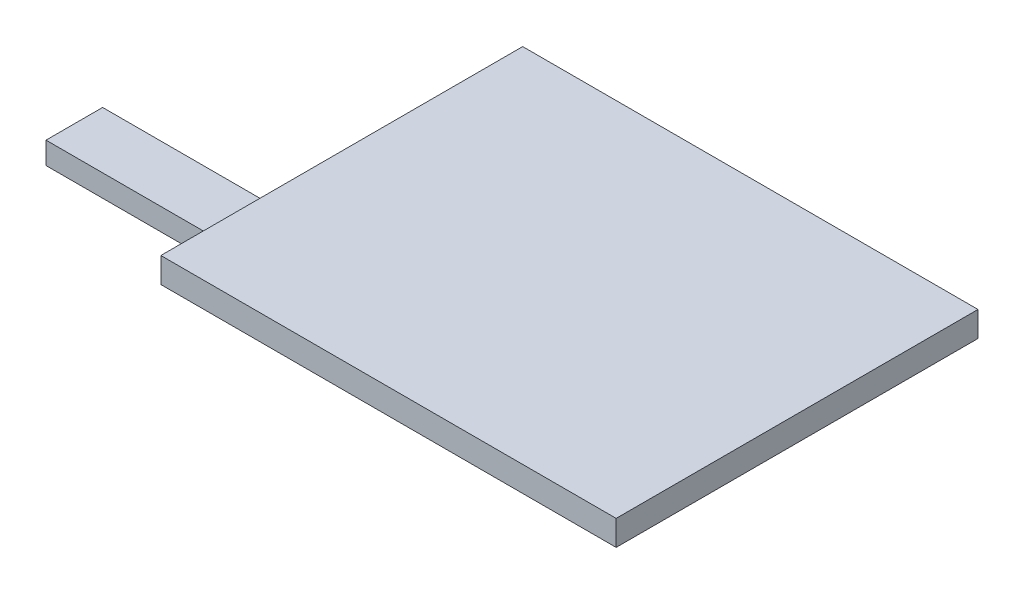
SolidWorks part; units mm, degrees
ref_plane "Front Plane" through (0, 0, 0) normal (0, 0, 1) x (1, 0, 0)
ref_plane "Top Plane" through (0, 0, 0) normal (0, 1, 0) x (1, 0, 0)
ref_plane "Right Plane" through (0, 0, 0) normal (1, 0, 0) x (0, 0, -1)
sketch "Sketch1" plane through (0, 0, 0) normal (0, 0, 1) x (1, 0, 0)
  line L0 (-37.4502, 11.0728) -> (107.2498, 11.0728)
  line L1 (107.2498, 11.0728) -> (107.2498, 3.0728)
  line L2 (107.2498, 3.0728) -> (-37.4502, 3.0728)
  line L3 (-37.4502, 3.0728) -> (-37.4502, 11.0728)
  dimension "D1" = 8
  dimension "D2" = 144.7
extrude "Boss-Extrude1" add sketch "Sketch1" along normal blind 115
sketch "Sketch2" plane through (0, 11.0728, 0) normal (0, 1, 0) x (1, 0, 0)
  line L0 (-37.4502, -57.5) -> (107.2498, -57.5) construction
  line L1 (-37.4502, -115) -> (-37.4502, 0) construction
  line L2 (107.2498, -115) -> (107.2498, 0) construction
sketch "Sketch3" plane through (0, 3.0728, 0) normal (0, -1, 0) x (1, 0, 0)
  line L0 (-37.4502, 77.5) -> (-10.4789, 77.5) construction
  line L1 (-37.4502, 115) -> (-37.4502, 0) construction
  line L2 (-37.4502, 57.5) -> (107.2498, 57.5) construction
  line L3 (-37.4502, 86.5) -> (-27.4502, 86.5)
  line L4 (-27.4502, 86.5) -> (-27.4502, 68.5)
  line L5 (-27.4502, 68.5) -> (-37.4502, 68.5)
  line L6 (-37.4502, 68.5) -> (-37.4502, 86.5)
  dimension "D1" = 20
  dimension "D2" = 10
  dimension "D3" = 9
  dimension "D4" = 9
extrude "Boss-Extrude2" add sketch "Sketch3" along normal blind 14
sketch "Sketch4" plane through (-37.4502, 0, 0) normal (-1, 0, 0) x (0, 0, 1)
  line L0 (68.5, -10.9272) -> (68.5, -3.9272)
  line L1 (68.5, -10.9272) -> (68.5, 3.0728) construction
  line L2 (68.5, -3.9272) -> (86.5, -3.9272)
  line L3 (86.5, -10.9272) -> (86.5, 3.0728) construction
  line L4 (86.5, -3.9272) -> (86.5, -10.9272)
  line L5 (86.5, -10.9272) -> (68.5, -10.9272)
  dimension "D1" = 7
sketch "Sketch5" plane through (0, 0, 86.5) normal (0, 0, 1) x (1, 0, 0)
  line L0 (-37.4502, 3.0728) -> (-27.4502, 3.0728)
  line L1 (-27.4502, 3.0728) -> (-27.4502, -3.9272)
  line L2 (-27.4502, -10.9272) -> (-27.4502, 3.0728) construction
  line L4 (-37.4502, -10.9272) -> (-37.4502, 3.0728) construction
  line L5 (-37.4502, -3.9272) -> (-37.4502, 3.0728)
  line L6 (-27.4502, -3.9272) -> (-27.4502, -10.9272)
  line L7 (-27.4502, -10.9272) -> (-37.4502, -10.9272)
  line L8 (-27.4502, -10.9272) -> (-37.4502, -10.9272) construction
  line L9 (-37.4502, -10.9272) -> (-37.4502, -3.9272)
sketch "Sketch6" plane through (0, 0, 68.5) normal (0, 0, -1) x (-1, 0, 0)
  line L0 (37.4502, 3.0728) -> (27.4502, 3.0728)
  line L1 (27.4502, 3.0728) -> (27.4502, -3.9272)
  line L2 (27.4502, -10.9272) -> (27.4502, 3.0728) construction
  line L4 (37.4502, -10.9272) -> (37.4502, 3.0728) construction
  line L5 (37.4502, -3.9272) -> (37.4502, 3.0728)
  line L6 (27.4502, -3.9272) -> (27.4502, -10.9272)
  line L7 (27.4502, -10.9272) -> (37.4502, -10.9272)
  line L8 (37.4502, -10.9272) -> (37.4502, -3.9272)
extrude "Boss-Extrude6" add sketch "Sketch4" along normal blind 65
extrude "Boss-Extrude7" add sketch "Sketch5" along normal blind 10
extrude "Boss-Extrude8" add sketch "Sketch6" along normal blind 10
